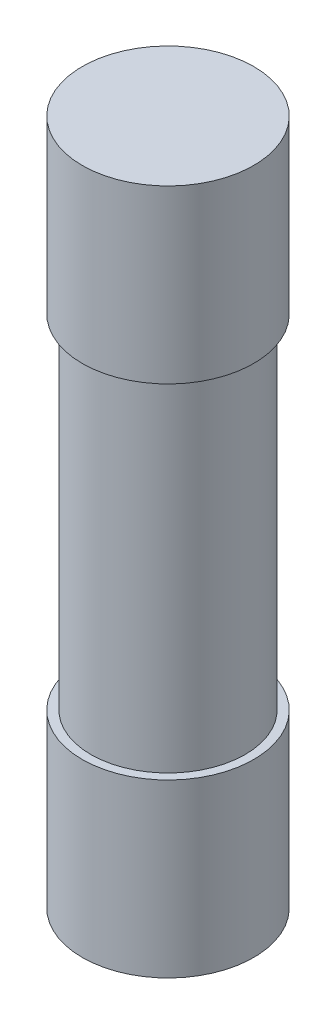
SolidWorks part; units mm, degrees
ref_plane "Front Plane" through (0, 0, 0) normal (0, 0, 1) x (1, 0, 0)
ref_plane "Top Plane" through (0, 0, 0) normal (0, 1, 0) x (1, 0, 0)
ref_plane "Right Plane" through (0, 0, 0) normal (1, 0, 0) x (0, 0, -1)
sketch "Sketch1" plane through (0, 0, 0) normal (0, 1, 0) x (1, 0, 0)
  circle A0 centre (0, 0) radius 2.5
  dimension "D1" = 5
extrude "Boss-Extrude1" add sketch "Sketch1" along normal blind 5
sketch "Sketch2" plane through (0, 5, 0) normal (0, 1, 0) x (1, 0, 0)
  circle A0 centre (0, 0) radius 2.25
  dimension "D1" = 4.5
extrude "Boss-Extrude2" add sketch "Sketch2" along normal blind 10 separate body
sketch "Sketch3" plane through (0, 15, 0) normal (0, 1, 0) x (1, 0, 0)
  circle A0 centre (0, 0) radius 2.5
  dimension "D1" = 5
extrude "Boss-Extrude3" add sketch "Sketch3" along normal blind 5 separate body contours A0
ref_point "Point1"
